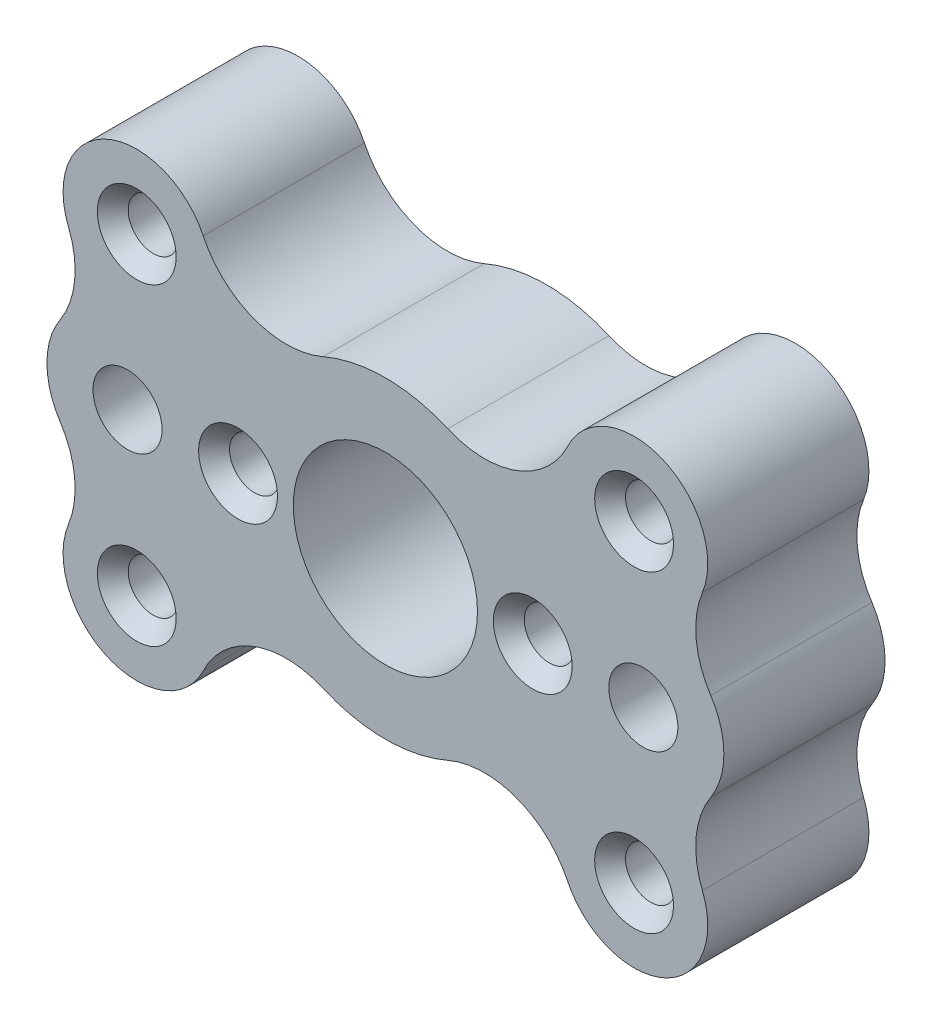
SolidWorks part; units mm, degrees
material "6061-T6 (SS)"
ref_plane "Front Plane" through (0, 0, 0) normal (0, 0, 1) x (1, 0, 0)
ref_plane "Top Plane" through (0, 0, 0) normal (0, 1, 0) x (1, 0, 0)
ref_plane "Right Plane" through (0, 0, 0) normal (1, 0, 0) x (0, 0, -1)
sketch "Sketch1" plane through (0, 0, 0) normal (0, 0, 1) x (1, 0, 0)
  line L0 (0, 0) -> (-10.16, 0) construction
  line L1 (5.6412, 6.35) -> (-10.16, 6.35) construction
  line L2 (-10.16, -6.35) -> (5.6412, -6.35) construction
  line L3 (0, 6.35) -> (0, 10.795)
  line L4 (0, -6.35) -> (0, -10.795)
  line L5 (0, 19.1525) -> (0, -23.4374) construction
  line L6 (0, 10.795) -> (-17.145, 10.795) construction
  line L7 (-17.145, 10.795) -> (-17.145, -10.795) construction
  line L8 (-17.145, -10.795) -> (0, -10.795) construction
  line L9 (-17.145, 10.795) -> (-13.6096, 5.3313) construction
  arc A0 (0, 6.35) -> (0, -6.35) centre (0, 0) ccw
  circle A1 centre (-10.16, 0) radius 2.159 construction
  arc A2 (-10.16, 6.35) -> (-10.16, -6.35) centre (-10.16, 0) ccw construction
  circle A3 centre (-17.78, 0) radius 2.3813
  arc A4 (0, 10.795) -> (-4.3021, 9.9007) centre (0, 0) ccw
  arc A5 (-12.5618, 12.986) -> (-21.8558, 8.8937) centre (-17.145, 10.795) ccw
  arc A6 (-4.3021, 9.9007) -> (-12.5618, 12.986) centre (-6.8327, 15.7247) cw
  arc A7 (-22.43, 3.0413) -> (-22.43, -3.0413) centre (-17.78, 0) ccw
  arc A8 (-21.8558, -8.8937) -> (-12.5618, -12.986) centre (-17.145, -10.795) ccw
  arc A9 (-12.5618, -12.986) -> (-4.3021, -9.9007) centre (-6.8327, -15.7247) cw
  arc A10 (0, -10.795) -> (-4.3021, -9.9007) centre (0, 0) cw
  arc A11 (-22.43, 3.0413) -> (-21.8558, 8.8937) centre (-27.7443, 6.5171) ccw
  arc A12 (-21.8558, -8.8937) -> (-22.43, -3.0413) centre (-27.7443, -6.5171) ccw
  point P19 (-17.145, 0)
  dimension "D1" = 12.7
  dimension "D3" = 4.318
  dimension "D4" = 12.7
  dimension "D5" = 35.56
  dimension "D7" = 4.7625
  dimension "D11" = 4.445
  dimension "D12" = 10.16
  dimension "D13" = 6.35
  dimension "D14" = 3.175
  dimension "D2" = 10.16
  dimension "D8" = 21.59
  dimension "D9" = 34.29
  dimension "D10" = 6.5078
extrude "Boss-Extrude1" add sketch "Sketch1" along normal blind 11.1125 contours A5 A7 A8 A9 A10 L4 A0 L3 A4 A6
hole_wizard "#8-32 Tapped Hole1" positions "Sketch3" profile "Sketch2" tap size "#8-32" standard "ANSI Inch" end condition through all
sketch "Sketch3" plane through (0, 0, 11.1125) normal (0, 0, 1) x (1, 0, 0)
  point P0 (-10.16, 0)
  point P3 (-17.145, 10.795)
  point P6 (-17.145, -10.795)
cosmetic thread "Hole Thread1" parameters "D2"=4.1656
cosmetic thread "Hole Thread2" parameters "D2"=4.1656
cosmetic thread "Hole Thread3" parameters "D2"=4.1656
sketch "Sketch2" plane through (-10.16, 0, 11.1125) normal (1, 0, 0) x (0, -1, 0)
  line L0 (0, 0) -> (0, 11.1125)
  line L1 (0, 11.1125) -> (2.7292, 11.1125)
  line L2 (1.7272, 9.9598) -> (1.7272, 1.1396)
  line L3 (1.7272, 1.1396) -> (2.7178, 0)
  line L5 (2.7178, 0) -> (0, 0)
  line L6 (-1.7272, 1.1396) -> (-2.7178, 0) construction
  line L7 (2.7292, 11.1125) -> (1.7272, 9.9598)
  line L8 (-2.7292, 11.1125) -> (-1.7272, 9.9598) construction
  line L11 (0, -6.35) -> (0, 107.95) construction
  dimension "Thru Tap Drill Dia." = 3.4544
  dimension "Thru Tap Drill Depth" = 11.1125
  dimension "Near C'Sink Dia." = 5.4356
  dimension "Near C'Sink Angle" = 82
  dimension "Far C'Sink Dia." = 5.4585
  dimension "Far C'Sink Angle" = 82
mirror "Mirror2" about plane through (0, 6.35, 11.1125) normal (-1, 0, 0) of bodies 102
sketch "Sketch4" [suppressed] plane through (0, 0, 11.1125) normal (0, 0, 1) x (1, 0, 0)
  line L0 (38.1, -123.825) -> (38.1, 28.575) construction
  line L1 (38.1, -116.205) -> (30.48, -116.205)
  line L2 (38.1, -116.205) -> (38.1, -123.825)
  line L3 (38.1, -123.825) -> (30.48, -123.825)
  line L4 (30.48, -116.205) -> (30.48, -123.825)
  line L5 (38.1, -116.205) -> (30.48, -123.825) construction
  line L6 (38.1, -123.825) -> (30.48, -116.205) construction
  line L7 (38.1, -123.825) -> (-38.1, -123.825) construction
  line L8 (38.1, 28.575) -> (-38.1, 28.575) construction
  line L9 (-38.1, -123.825) -> (-38.1, 28.575) construction
  line L10 (-28.575, -22.225) -> (28.575, -22.225) construction
  line L11 (-28.575, -22.225) -> (-28.575, 22.225) construction
  line L12 (28.575, -22.225) -> (28.575, 22.225) construction
  line L13 (-28.575, 22.225) -> (28.575, 22.225) construction
  line L14 (28.575, 22.225) -> (-28.575, -22.225) construction
  line L15 (-38.1, 0) -> (38.1, 0) construction
  line L16 (-28.575, -70.485) -> (-28.575, -26.035) construction
  line L17 (-28.575, -70.485) -> (28.575, -70.485) construction
  line L18 (-28.575, -26.035) -> (28.575, -26.035) construction
  line L19 (28.575, -70.485) -> (28.575, -26.035) construction
  line L20 (-28.575, -74.295) -> (28.575, -74.295) construction
  line L21 (-28.575, -74.295) -> (-28.575, -118.745) construction
  line L22 (28.575, -74.295) -> (28.575, -118.745) construction
  line L23 (-28.575, -118.745) -> (28.575, -118.745) construction
  line L24 (0, -74.295) -> (0, -70.485) construction
  line L25 (0, -26.035) -> (0, -22.225) construction
  arc A0 (-12.5618, 12.986) -> (-21.8558, 8.8937) centre (-17.145, 10.795) ccw construction
  arc A1 (21.8558, 8.8937) -> (12.5618, 12.986) centre (17.145, 10.795) ccw construction
  point P4 (34.29, -120.015)
  dimension "D3" = 6.35
  dimension "D4" = 6.35
  dimension "D1" = 152.4
  dimension "D2" = 76.2
  dimension "D5" = 7.62
  dimension "D6" = 6.35
  dimension "D7" = 3.81
  dimension "D8" = 48.26
extrude "Boss-Extrude2" [suppressed] add sketch "Sketch4" against normal up to surface (11.1125 mm away) separate body
sketch "Sketch5" [suppressed] plane through (0, 0, 0) normal (0, 0, -1) x (-1, 0, 0)
  line L0 (4.3021, 9.9007) -> (-4.3021, 9.9007)
  line L1 (4.3021, 9.9007) -> (4.3021, 15.7992)
  line L2 (-4.3021, 9.9007) -> (-4.3021, 15.7992)
  line L3 (4.3021, 15.7992) -> (-4.3021, 15.7992)
  line L4 (-4.3021, -9.9007) -> (4.3021, -9.9007)
  line L5 (-4.3021, -9.9007) -> (-4.3021, -15.0034)
  line L6 (4.3021, -9.9007) -> (4.3021, -15.0034)
  line L7 (-4.3021, -15.0034) -> (4.3021, -15.0034)
  line L8 (-22.43, -3.0413) -> (-22.43, 3.0413)
  line L9 (-22.43, -3.0413) -> (-26.2695, -3.0413)
  line L10 (-22.43, 3.0413) -> (-26.2695, 3.0413)
  line L11 (-26.2695, -3.0413) -> (-26.2695, 3.0413)
  line L12 (22.43, -3.0413) -> (22.43, 3.0413)
  line L13 (22.43, -3.0413) -> (26.1216, -3.0413)
  line L14 (22.43, 3.0413) -> (26.1216, 3.0413)
  line L15 (26.1216, -3.0413) -> (26.1216, 3.0413)
extrude "Boss-Extrude4" [suppressed] add sketch "Sketch5" against normal blind 1.27
